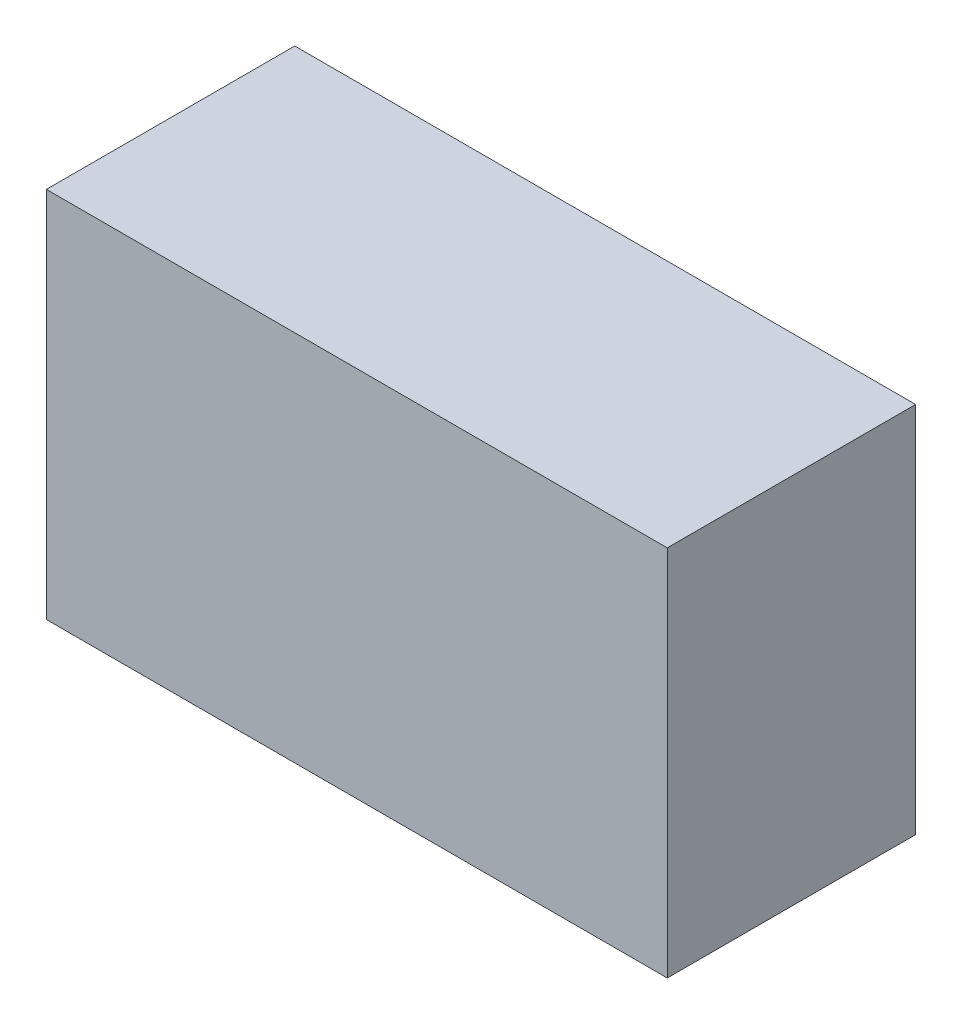
SolidWorks part; units mm, degrees
ref_plane "前视基准面" through (0, 0, 0) normal (0, 0, 1) x (1, 0, 0)
ref_plane "上视基准面" through (0, 0, 0) normal (0, 1, 0) x (1, 0, 0)
ref_plane "右视基准面" through (0, 0, 0) normal (1, 0, 0) x (0, 0, -1)
sketch "草图1" plane through (0, 0, 0) normal (0, 0, 1) x (1, 0, 0)
  line L1 (-4.1875, 11.1562) -> (20.8125, 11.1562)
  line L2 (-4.1875, 11.1562) -> (-4.1875, -3.8438)
  line L3 (-4.1875, -3.8438) -> (20.8125, -3.8438)
  line L4 (20.8125, 11.1562) -> (20.8125, -3.8438)
  dimension "D1" = 15
  dimension "D2" = 25
extrude "凸台-拉伸1" add sketch "草图1" along normal blind 10
scale "缩放比例1" bodies to scale 101 scale about centroid uniform scaling yes scale factor 0.7
